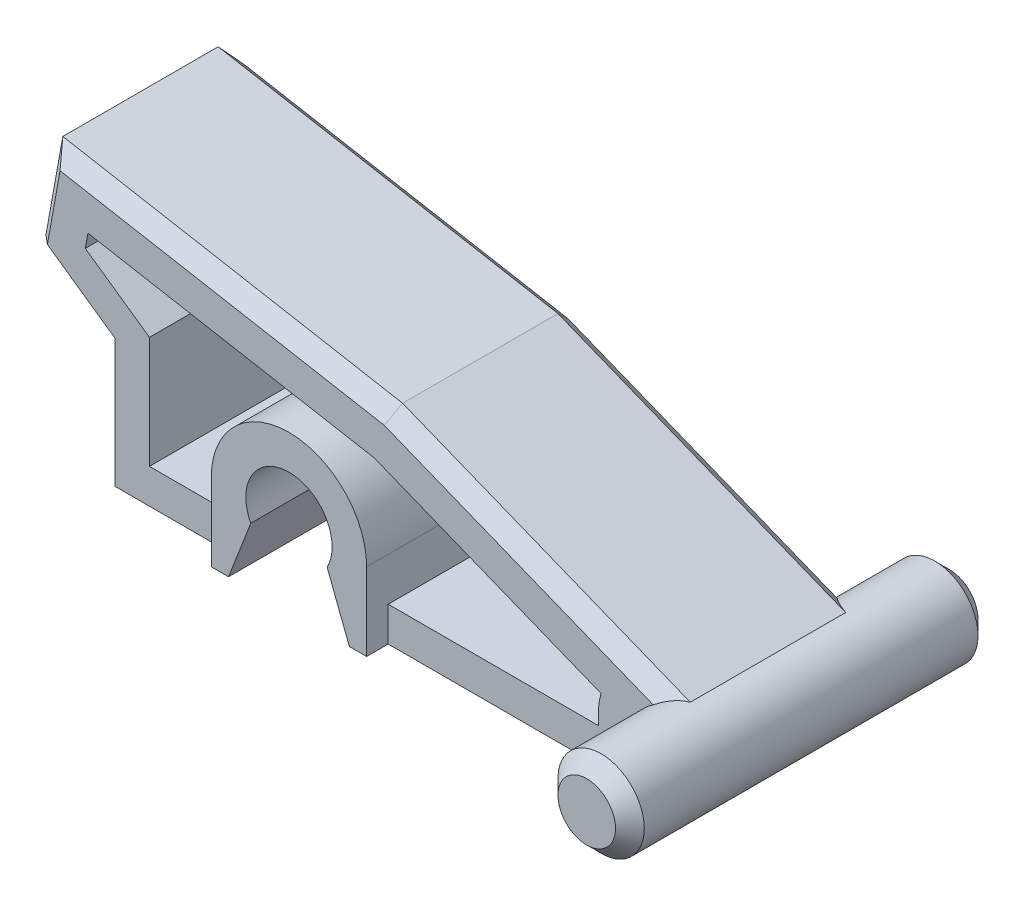
SolidWorks part; units mm, degrees
ref_plane "Front Plane" through (0, 0, 0) normal (0, 0, 1) x (1, 0, 0)
ref_plane "Top Plane" through (0, 0, 0) normal (0, 1, 0) x (1, 0, 0)
ref_plane "Right Plane" through (0, 0, 0) normal (1, 0, 0) x (0, 0, -1)
sketch "Sketch1" plane through (0, 0, 0) normal (0, 0, 1) x (1, 0, 0)
  line L0 (10, -4.4) -> (10, -1.4)
  line L1 (-10, -4.4) -> (10, -4.4)
  line L2 (-10, -4.4) -> (-10, 4.4)
  line L3 (-10, 4.4) -> (10, 4.4)
  line L4 (10, -4.4) -> (10, 4.4)
  line L5 (-10, -4.4) -> (10, 4.4) construction
  line L6 (-10, 4.4) -> (10, -4.4) construction
  line L7 (10, -1.4) -> (0, 2.6)
  line L8 (0, 2.6) -> (-11.8102, 4.7258)
  line L9 (-11.8102, 4.7258) -> (-12.3948, 1.478)
  line L10 (-12.3948, 1.478) -> (-10, -0.2)
  point P0 (0, 0)
  dimension "D1" = 20
  dimension "D2" = 8.8
  dimension "D3" = 3
  dimension "D4" = 7
  dimension "D5" = 10
  dimension "D6" = 12
  dimension "D7" = 3.3
  dimension "D8" = 4.2
extrude "Boss-Extrude1" add sketch "Sketch1" along normal mid plane 6.4 contours L7 L8 L2 L1 L0 | L9 L10 L2 L8
sketch "Sketch2" plane through (0, 0, 3.2) normal (0, 0, 1) x (1, 0, 0)
  line L0 (-10, -4.4) -> (10, -4.4) construction
  line L1 (-10, -4.4) -> (-10, -0.2) construction
  line L2 (-5.4, -1.7) -> (-5.4, -4.4)
  line L3 (-5.4, -4.4) -> (-2.7, -4.4)
  line L4 (-2.7, -4.4) -> (-5.4, -1.7)
  line L5 (-2.7, -4.4) -> (0, -4.4)
  line L6 (0, -4.4) -> (0, -1.7)
  line L7 (0, -1.7) -> (-2.7, -4.4)
  circle A0 centre (-2.7, -1.7) radius 2.7
  line M13 (-10, -4.4) -> (10, -4.4)
  dimension "D1" = 5.4
  dimension "D2" = 7.3
extrude "Boss-Extrude2" add sketch "Sketch2" along normal mid plane 1.5 contours L7 A0 L4 | L4 A0 | L7 A0 | A0 L6 M13 | A0 L2 M13
mirror "Mirror1" about plane through (0, 0, 0) normal (0, 0, 1) of "Boss-Extrude2"
sketch "Sketch3" plane through (0, 0, 3.95) normal (0, 0, 1) x (1, 0, 0)
  line L0 (-4.8, -4.4) -> (-0.6, -4.4)
  line L1 (-5.4, -4.4) -> (0, -4.4) construction
  line L2 (-4.8, -4.4) -> (-4.0266, -2.4)
  line L3 (-4.0266, -2.4) -> (-1.3734, -2.4)
  line L4 (-1.3734, -2.4) -> (-0.6, -4.4)
  circle A0 centre (-2.7, -1.7) radius 1.5
  point P8 (-2.7, -4.4)
  line M5 (-5.4, -4.4) -> (0, -4.4)
  dimension "D1" = 3
  dimension "D2" = 4.2
  dimension "D3" = 0
  dimension "D4" = 2
extrude "Cut-Extrude1" cut sketch "Sketch3" against normal through all both and the other way through all contours L3 A0 | A0 L2 L4 M5
sketch "Sketch4" plane through (0, 0, 0) normal (0, 0, 1) x (1, 0, 0)
  line L0 (10, -4.4) -> (10, -1.4) construction
  circle A0 centre (10, -2.9) radius 1.5
extrude "Boss-Extrude3" add sketch "Sketch4" along normal mid plane 12.6
chamfer "Chamfer1" distance 0.5 angle 45 2 edges at (11.5, -2.9, -6.3) (11.5, -2.9, 6.3)
chamfer "Chamfer2" distance 0.5 angle 45 10 edges at (-10, -2.3, 3.2) (-11.1974, 0.639, 3.2) (-12.1025, 3.1019, 3.2) (-5.9051, 3.6629, 3.2) (5, 0.6, 3.2) (-10, -2.3, -3.2) (-11.1974, 0.639, -3.2) (-12.1025, 3.1019, -3.2) (-5.9051, 3.6629, -3.2) (5, 0.6, -3.2)
sketch "Sketch5" plane through (0, 0, 3.2) normal (0, 0, 1) x (1, 0, 0)
  line L0 (-10.5291, 2.2466) -> (-10.4382, 2.7516)
  line L1 (-10.4382, 2.7516) -> (-0.4711, 0.9575)
  line L2 (-0.4711, 0.9575) -> (7.3953, -2.1891)
  line L3 (7.3167, -3.2) -> (0, -3.2)
  line L4 (0, -1.7) -> (0, -4.4) construction
  line L5 (-10.5291, 2.2466) -> (-8.3, 0.6846)
  line L6 (-8.3, 0.6846) -> (-8.3, -3.2)
  line L7 (-8.3, -3.2) -> (-5.4, -3.2)
  line L8 (-5.4, -4.4) -> (-5.4, -1.7) construction
  line L9 (-11.4067, 4.1452) -> (-11.8461, 1.7041) construction
  line L10 (-0.1386, 2.1169) -> (-11.4067, 4.1452) construction
  line L11 (9.2123, -1.6234) -> (-0.1386, 2.1169) construction
  line L12 (0, -4.4) -> (10, -4.4) construction
  line L15 (-9.5, -4.4) -> (-5.4, -4.4) construction
  line L16 (-9.5, 0.0602) -> (-9.5, -4.4) construction
  line L17 (-11.8461, 1.7041) -> (-9.5, 0.0602) construction
  line L18 (-5.4, -3.2) -> (-5.4, -1.7)
  line L19 (0, -3.2) -> (0, -1.7)
  circle A0 centre (10, -2.9) radius 2.7
  circle A1 centre (10, -2.9) radius 1.5 construction
  circle A2 centre (-2.7, -1.7) radius 2.7
  line M14 (-5.4, -4.4) -> (-5.4, -1.7)
  arc M15 (-5.4, -1.7) -> (0, -1.7) centre (-2.7, -1.7) cw
  line M16 (0, -1.7) -> (0, -4.4)
  dimension "D4" = 1.2
  dimension "D9" = 5.4
  dimension "D1" = 1.2
  dimension "D2" = 1.2
  dimension "D3" = 1.2
  dimension "D5" = 1.2
  dimension "D6" = 1.2
  dimension "D7" = 1.2
  dimension "D8" = 1.2
extrude "Cut-Extrude2" cut sketch "Sketch5" against normal offset from surface (5.2 mm away) 1.2 contours A0 L2 L1 L0 L5 L6 L7 L3 M14 M15 M16 up to face at (-3.1844, -1.1086, -3.2)
